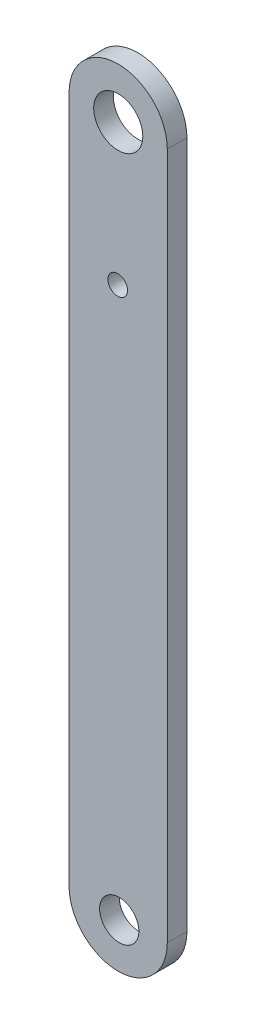
SolidWorks part; units mm, degrees
ref_plane "Front Plane" through (0, 0, 0) normal (0, 0, 1) x (1, 0, 0)
ref_plane "Top Plane" through (0, 0, 0) normal (0, 1, 0) x (1, 0, 0)
ref_plane "Right Plane" through (0, 0, 0) normal (1, 0, 0) x (0, 0, -1)
sketch "Sketch1" plane through (0, 0, 0) normal (0, 0, 1) x (1, 0, 0)
  line L0 (-23.3407, 36.8293) -> (-23.3407, -33.1707)
  line L2 (-13.3407, -33.1707) -> (-13.3407, 36.8293)
  arc A0 (-23.3407, 36.8293) -> (-13.3407, 36.8293) centre (-18.3407, 36.8293) cw
  arc A1 (-23.3407, -33.1707) -> (-13.3407, -33.1707) centre (-18.3407, -33.1707) ccw
  dimension "D1" = 5
  dimension "D2" = 70
extrude "Boss-Extrude1" add sketch "Sketch1" along normal blind 2
sketch "Sketch2" plane through (0, 0, 2) normal (0, 0, 1) x (1, 0, 0)
  line L0 (-18.336, 34.2097) -> (-18.336, 23.4597) construction
  circle A0 centre (-18.336, 36.7097) radius 2.5
  circle A1 centre (-18.3871, 22.3305) radius 1
  circle A2 centre (-18.2332, -33.5915) radius 2
  dimension "D1" = 5
  dimension "D3" = 2
  dimension "D4" = 4
  dimension "D2" = 10.75
extrude "Cut-Extrude1" cut sketch "Sketch2" against normal blind 2
